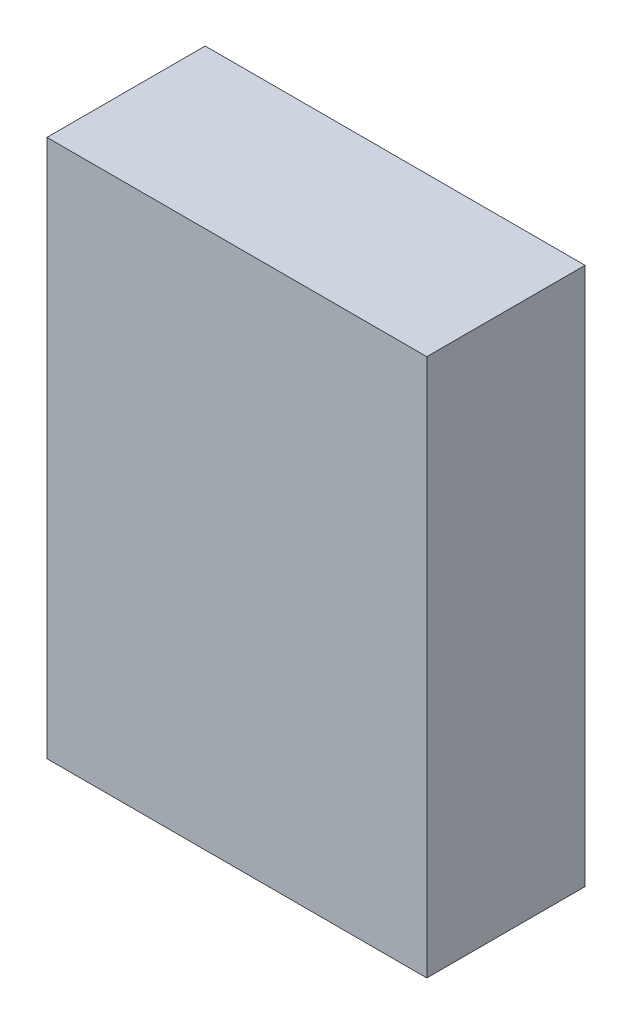
SolidWorks part; units mm, degrees
ref_plane "Front Plane" through (0, 0, 0) normal (0, 0, 1) x (1, 0, 0)
ref_plane "Top Plane" through (0, 0, 0) normal (0, 1, 0) x (1, 0, 0)
ref_plane "Right Plane" through (0, 0, 0) normal (1, 0, 0) x (0, 0, -1)
sketch "Sketch1" plane through (0, 0, 0) normal (0, 0, 1) x (1, 0, 0)
  line L1 (-60, 85) -> (60, 85)
  line L2 (-60, 85) -> (-60, -85)
  line L3 (-60, -85) -> (60, -85)
  line L4 (60, 85) -> (60, -85)
  line L5 (-60, 85) -> (60, -85) construction
  line L6 (-60, -85) -> (60, 85) construction
  point P0 (0, 0)
  dimension "D1" = 170
  dimension "D2" = 120
extrude "Boss-Extrude1" add sketch "Sketch1" along normal blind 50
